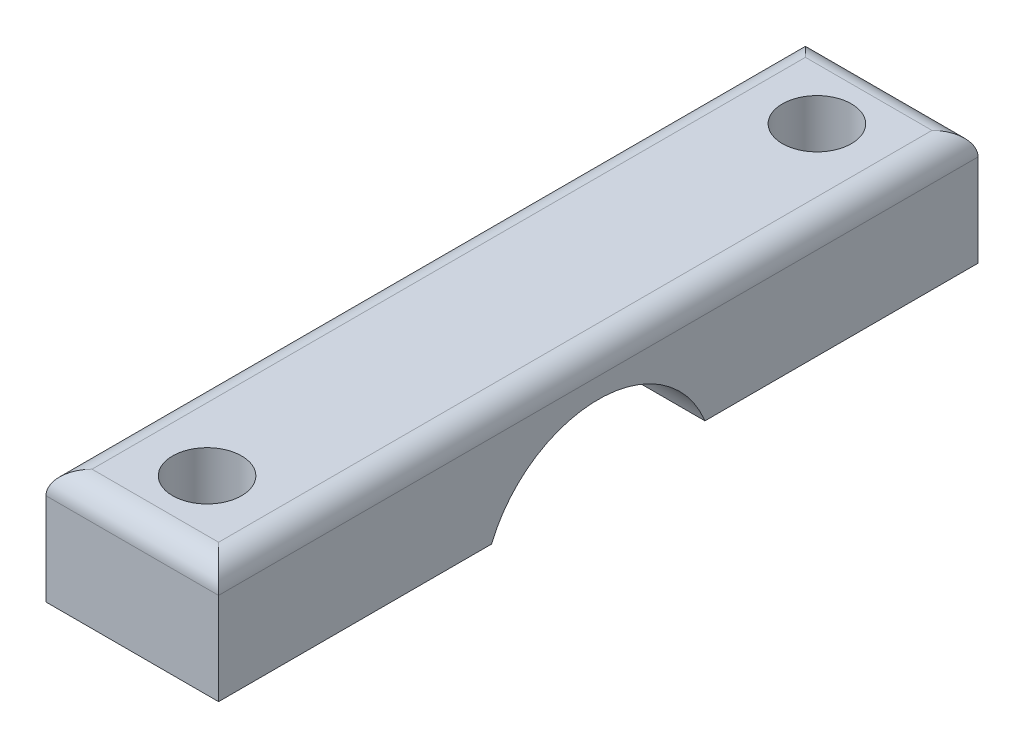
SolidWorks part; units mm, degrees
ref_plane "Front Plane" through (0, 0, 0) normal (0, 0, 1) x (1, 0, 0)
ref_plane "Top Plane" through (0, 0, 0) normal (0, 1, 0) x (1, 0, 0)
ref_plane "Right Plane" through (0, 0, 0) normal (1, 0, 0) x (0, 0, -1)
sketch "Sketch1" plane through (0, 0, 0) normal (0, 1, 0) x (1, 0, 0)
  line L0 (7.5, 66) -> (7.5, 0) construction
  line L1 (0, 0) -> (15, 0)
  line L2 (0, 0) -> (0, 66)
  line L3 (0, 66) -> (15, 66)
  line L4 (15, 0) -> (15, 66)
  line L5 (0, 33) -> (15, 33) construction
  circle A0 centre (7.5, 59.5) radius 1.75
  circle A1 centre (7.5, 6.5) radius 1.75
  dimension "D5" = 3.5
  dimension "D1" = 66
  dimension "D2" = 15
  dimension "D3" = 53
  dimension "D4" = 26.5
extrude "Boss-Extrude1" add sketch "Sketch1" along normal blind 10
sketch "Sketch2" plane through (0, 10, 0) normal (0, 1, 0) x (1, 0, 0)
  circle A0 centre (7.5, 59.5) radius 3
  circle A1 centre (7.5, 6.5) radius 3
  dimension "D1" = 6
  dimension "D2" = 6
extrude "Cut-Extrude1" cut sketch "Sketch2" against normal blind 6
fillet "Fillet1" radius 2 4 edges at (7.5, 10, -66) (0, 10, -33) (7.5, 10, 0) (15, 10, -33)
sketch "Sketch3" plane through (15, 0, 0) normal (1, 0, 0) x (0, 0, -1)
  line L0 (33, 0) -> (33, 10) construction
  line L1 (0, 0) -> (66, 0) construction
  line L2 (2, 10) -> (64, 10) construction
  circle A0 centre (33, -3.75) radius 10
  dimension "D2" = 20
  dimension "D1" = 3.75
extrude "Cut-Extrude2" cut sketch "Sketch3" against normal blind 15
